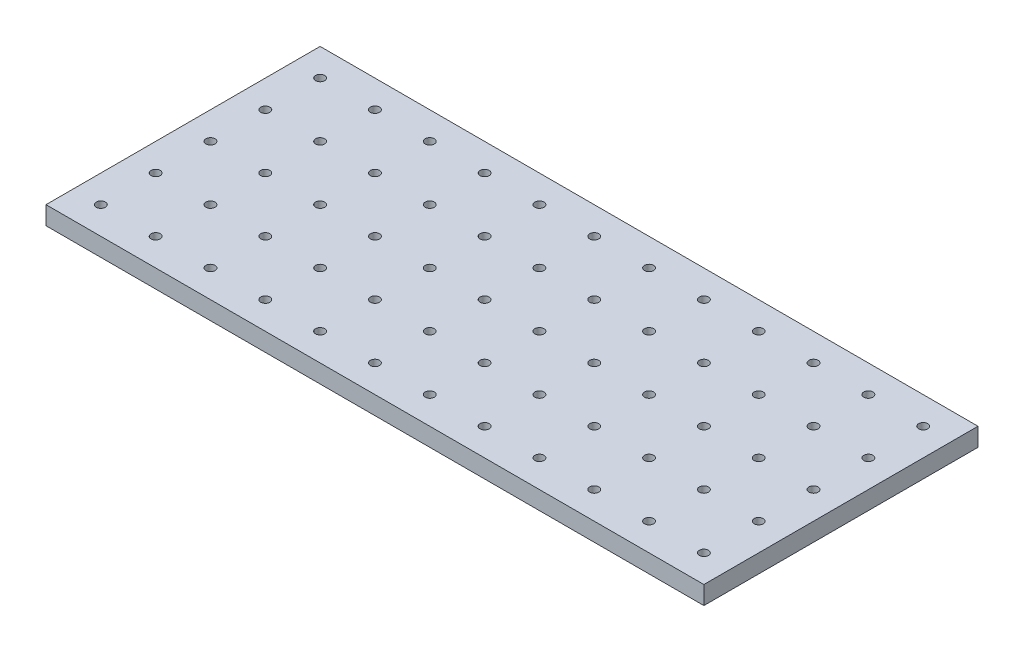
SolidWorks part; units mm, degrees
ref_plane "Front Plane" through (0, 0, 0) normal (0, 0, 1) x (1, 0, 0)
ref_plane "Top Plane" through (0, 0, 0) normal (0, 1, 0) x (1, 0, 0)
ref_plane "Right Plane" through (0, 0, 0) normal (1, 0, 0) x (0, 0, -1)
sketch "Sketch2" plane through (0, 0, 0) normal (0, 1, 0) x (1, 0, 0)
  line L1 (-1800, 750) -> (1800, 750)
  line L2 (-1800, 750) -> (-1800, -750)
  line L3 (-1800, -750) -> (1800, -750)
  line L4 (1800, 750) -> (1800, -750)
  line L5 (-1800, 750) -> (1800, -750) construction
  line L6 (-1800, -750) -> (1800, 750) construction
  point P0 (0, 0)
  dimension "D1" = 3600
  dimension "D2" = 1500
extrude "Boss-Extrude1" add sketch "Sketch2" along normal blind 100
sketch "Sketch3" plane through (0, 100, 0) normal (0, 1, 0) x (1, 0, 0)
  line L1 (-1800, 750) -> (-1650, 750) construction
  line L2 (-1800, 750) -> (-1800, 600) construction
  line L3 (-1800, 600) -> (-1650, 600) construction
  line L4 (-1650, 750) -> (-1650, 600) construction
  circle A0 centre (-1650, 600) radius 25
  circle A1 centre (-1350, 600) radius 25
  circle A2 centre (-1050, 600) radius 25
  circle A3 centre (-750, 600) radius 25
  circle A4 centre (-450, 600) radius 25
  circle A5 centre (-150, 600) radius 25
  circle A6 centre (150, 600) radius 25
  circle A7 centre (450, 600) radius 25
  circle A8 centre (750, 600) radius 25
  circle A9 centre (1050, 600) radius 25
  circle A10 centre (1350, 600) radius 25
  circle A11 centre (1650, 600) radius 25
  circle A12 centre (-1350, 300) radius 25
  circle A13 centre (-1050, 300) radius 25
  circle A14 centre (-750, 300) radius 25
  circle A15 centre (-450, 300) radius 25
  circle A16 centre (-150, 300) radius 25
  circle A17 centre (150, 300) radius 25
  circle A18 centre (450, 300) radius 25
  circle A19 centre (750, 300) radius 25
  circle A20 centre (1050, 300) radius 25
  circle A21 centre (1350, 300) radius 25
  circle A22 centre (1650, 300) radius 25
  circle A23 centre (-1350, 0) radius 25
  circle A24 centre (-1050, 0) radius 25
  circle A25 centre (-750, 0) radius 25
  circle A26 centre (-450, 0) radius 25
  circle A27 centre (-150, 0) radius 25
  circle A28 centre (150, 0) radius 25
  circle A29 centre (450, 0) radius 25
  circle A30 centre (750, 0) radius 25
  circle A31 centre (1050, 0) radius 25
  circle A32 centre (1350, 0) radius 25
  circle A33 centre (1650, 0) radius 25
  circle A34 centre (-1350, -300) radius 25
  circle A35 centre (-1050, -300) radius 25
  circle A36 centre (-750, -300) radius 25
  circle A37 centre (-450, -300) radius 25
  circle A38 centre (-150, -300) radius 25
  circle A39 centre (150, -300) radius 25
  circle A40 centre (450, -300) radius 25
  circle A41 centre (750, -300) radius 25
  circle A42 centre (1050, -300) radius 25
  circle A43 centre (1350, -300) radius 25
  circle A44 centre (1650, -300) radius 25
  circle A45 centre (-1350, -600) radius 25
  circle A46 centre (-1050, -600) radius 25
  circle A47 centre (-750, -600) radius 25
  circle A48 centre (-450, -600) radius 25
  circle A49 centre (-150, -600) radius 25
  circle A50 centre (150, -600) radius 25
  circle A51 centre (450, -600) radius 25
  circle A52 centre (750, -600) radius 25
  circle A53 centre (1050, -600) radius 25
  circle A54 centre (1350, -600) radius 25
  circle A55 centre (1650, -600) radius 25
  circle A56 centre (-1650, 300) radius 25
  circle A57 centre (-1650, 0) radius 25
  circle A58 centre (-1650, -300) radius 25
  circle A59 centre (-1650, -600) radius 25
  dimension "D2" = 50
  dimension "D1" = 150
  dimension "D3" = 12
  dimension "D4" = 5
extrude "Cut-Extrude1" cut sketch "Sketch3" against normal blind 100
